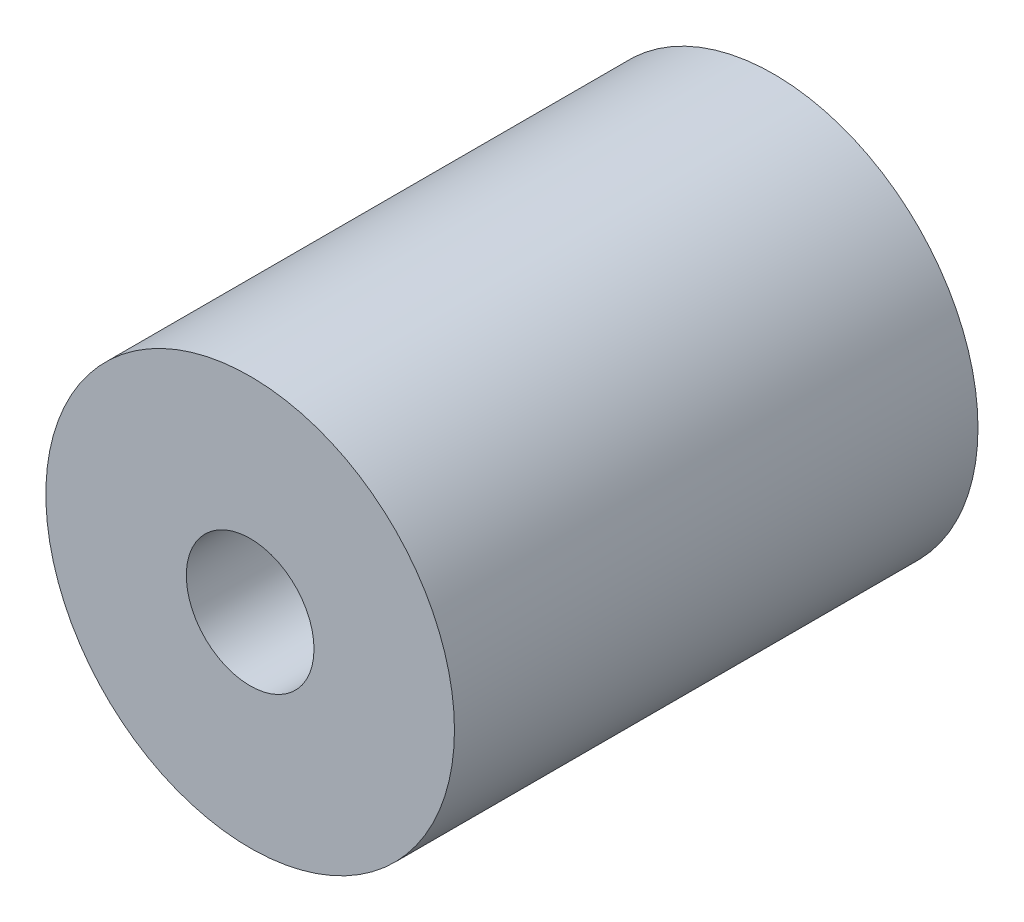
SolidWorks part; units mm, degrees
material "SKD11淬火HRC56-60"
ref_plane "前基準面" through (0, 0, 0) normal (0, 0, 1) x (1, 0, 0)
ref_plane "上基準面" through (0, 0, 0) normal (0, 1, 0) x (1, 0, 0)
ref_plane "右基準面" through (0, 0, 0) normal (1, 0, 0) x (0, 0, -1)
sketch "草图1" plane through (0, 0, 0) normal (0, 0, 1) x (1, 0, 0)
  circle A0 centre (0, 0) radius 16
  dimension "D1" = 32
extrude "凸台-拉伸1" add sketch "草图1" along normal blind 41
sketch "草图2" plane through (0, 0, 41) normal (0, 0, 1) x (1, 0, 0)
  circle A0 centre (0, 0) radius 5
  dimension "D1" = 10
extrude "切除-拉伸1" cut sketch "草图2" against normal through all
sketch "草图3" plane through (0, 0, 0) normal (0, 0, -1) x (-1, 0, 0)
  circle A0 centre (0, 0) radius 7
  dimension "D1" = 14
extrude "切除-拉伸2" cut sketch "草图3" against normal blind 12
